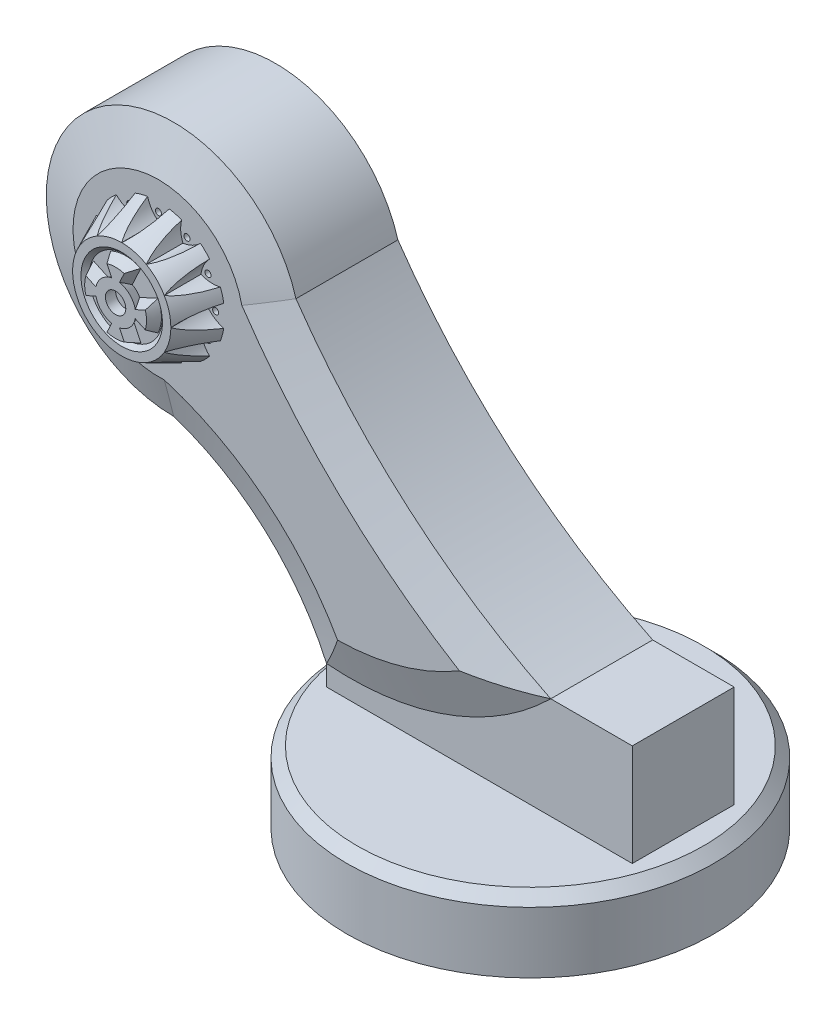
SolidWorks part; units mm, degrees
ref_plane "Front Plane" through (0, 0, 0) normal (0, 0, 1) x (1, 0, 0)
ref_plane "Top Plane" through (0, 0, 0) normal (0, 1, 0) x (1, 0, 0)
ref_plane "Right Plane" through (0, 0, 0) normal (1, 0, 0) x (0, 0, -1)
sketch "Sketch1" plane through (0, 0, 0) normal (0, 1, 0) x (1, 0, 0)
  circle A0 centre (0, 0) radius 90
  dimension "D1" = 180
extrude "Boss-Extrude1" add sketch "Sketch1" along normal blind 35
chamfer "Chamfer1" distance 5 angle 45 1 edges at (0, 35, 90)
sketch "Sketch2" plane through (0, 35, 0) normal (0, 1, 0) x (1, 0, 0)
  line L1 (-75, 25) -> (75, 25)
  line L2 (-75, 25) -> (-75, -25)
  line L3 (-75, -25) -> (75, -25)
  line L4 (75, 25) -> (75, -25)
  line L5 (-75, 25) -> (75, -25) construction
  line L6 (-75, -25) -> (75, 25) construction
  point P0 (0, 0)
  dimension "D1" = 150
  dimension "D2" = 50
extrude "Boss-Extrude2" add sketch "Sketch2" along normal blind 50
sketch "Sketch4" plane through (0, 0, 25) normal (0, 0, 1) x (1, 0, 0)
  line L0 (-75, 45) -> (-75, 85)
  line L1 (-75, 85) -> (-75, 35) construction
  line L2 (-75, 85) -> (35, 85)
  line L3 (-75, 85) -> (75, 85) construction
  arc A0 (-75, 45) -> (35, 85) centre (-63.4632, 184.5238) ccw
  dimension "D3" = 140
  dimension "D1" = 40
  dimension "D2" = 110
extrude "Cut-Extrude1" cut sketch "Sketch4" against normal blind 50
sketch "Sketch5" plane through (0, 0, 0) normal (0, 0, 1) x (1, 0, 0)
  arc A0 (-90, 192.5) -> (-150, 112.5) centre (-150, 175) ccw
  arc A1 (-150, 112.5) -> (-75, 45) centre (-189.0071, -6.2579) cw
  arc A2 (-90, 192.5) -> (35, 85) centre (177.4828, 377.1021) ccw
  arc A3 (-75, 45) -> (35, 85) centre (-63.4632, 184.5238) ccw
  dimension "D3" = 125
  dimension "D4" = 125
  dimension "D5" = 325
  dimension "D6" = 140
  dimension "D1" = 150
  dimension "D2" = 175
  dimension "D7" = 125
extrude "Boss-Extrude3" add sketch "Sketch5" along normal mid plane 50 separate body
sketch "Sketch6" plane through (0, 0, 25) normal (0, 0, 1) x (1, 0, 0)
  arc A4 (-75, 45) -> (-150, 112.5) centre (-189.0071, -6.2579) ccw
  arc A5 (-75, 45) -> (35, 85) centre (-63.4632, 184.5238) ccw
  arc A6 (-90, 192.5) -> (35, 85) centre (177.4828, 377.1021) ccw
  arc A7 (-90, 192.5) -> (-150, 112.5) centre (-150, 175) ccw
  arc A8 (-75, 45) -> (-150, 112.5) centre (-189.0071, -6.2579) ccw
  arc A9 (-75, 45) -> (35, 85) centre (-63.4632, 184.5238) ccw
  arc A10 (-90, 192.5) -> (35, 85) centre (177.4828, 377.1021) ccw
  arc A11 (-90, 192.5) -> (-150, 112.5) centre (-150, 175) ccw
  dimension "D1" = 0
extrude "Boss-Extrude5" add sketch "Sketch6" along normal blind 7.5 draft 70
sketch "Sketch7" plane through (0, 0, 32.5) normal (0, 0, 1) x (1, 0, 0)
  circle A0 centre (-150, 175) radius 32.5
  arc A1 (-109.0554, 183.8681) -> (-147.1527, 133.203) centre (-150, 175) ccw construction
  dimension "D1" = 65
extrude "Boss-Extrude6" add sketch "Sketch7" along normal blind 18 draft 25
sketch "Sketch9" plane through (0, 0, 50.5) normal (0, 0, 1) x (1, 0, 0)
  line L0 (-150, 175) -> (-150, 207.5) construction
  circle A0 centre (-150, 175) radius 32.5 construction
  arc A1 (-150, 199.1065) -> (-144.6801, 207.0616) centre (-159.1575, 210.9867) ccw
  circle A3 centre (-150, 175) radius 32.5
  arc A4 (-144.6801, 207.0616) -> (-155.3199, 207.0616) centre (-150, 175) ccw
  circle A5 centre (-150, 175) radius 24.1065 construction
  arc A6 (-150, 199.1065) -> (-155.3199, 207.0616) centre (-140.8425, 210.9867) cw
  dimension "D1" = 0
  dimension "D2" = 15
extrude "Cut-Extrude2" cut sketch "Sketch9" against normal up to surface (18 mm away) up to face at (-117.5, 175, 32.5)
sketch "Sketch10" plane through (0, 0, 32.5) normal (0, 0, 1) x (1, 0, 0)
  line L0 (-150, 199.1065) -> (-150, 207.0616) construction
  line L1 (-155.3199, 207.0616) -> (-144.6801, 207.0616) construction
  circle A2 centre (-150, 203.0841) radius 1.5
  dimension "D1" = 3
extrude "Cut-Extrude3" cut sketch "Sketch10" against normal blind 5
pattern_circular "CirPattern1" count 12 over 360 about axis through (-150, 175, 0) along (0, 0, 1) of "Cut-Extrude2", "Cut-Extrude3"
sketch "Sketch11" plane through (0, 0, 50.5) normal (0, 0, 1) x (1, 0, 0)
  circle A0 centre (-150, 175) radius 20
  dimension "D1" = 40
extrude "Cut-Extrude4" cut sketch "Sketch11" against normal blind 2 draft 45
sketch "Sketch12" plane through (0, 0, 48.5) normal (0, 0, 1) x (1, 0, 0)
  line L0 (-150, 175) -> (-150, 192.5) construction
  line L1 (-153.1696, 181.7973) -> (-157.3958, 190.8604)
  line L2 (-146.8304, 181.7973) -> (-142.6042, 190.8604)
  arc A0 (-146.8304, 181.7973) -> (-153.1696, 181.7973) centre (-150, 175) ccw
  arc A1 (-142.6042, 190.8604) -> (-157.3958, 190.8604) centre (-150, 175) ccw
  dimension "D1" = 15
  dimension "D2" = 35
  dimension "D3" = 25
extrude "Boss-Extrude7" add sketch "Sketch12" along normal blind 5 draft 25
pattern_circular "CirPattern2" count 4 over 360 about axis through (-150, 175, 0) along (0, 0, 1) of "Boss-Extrude7"
sketch "Sketch13" plane through (0, 0, 48.5) normal (0, 0, 1) x (1, 0, 0)
  circle A0 centre (-150, 175) radius 7.5
extrude "Boss-Extrude8" add sketch "Sketch13" along normal up to surface (5 mm away) draft 25
sketch "Sketch14" plane through (0, 0, 53.5) normal (0, 0, 1) x (1, 0, 0)
  circle A0 centre (-150, 175) radius 5
  dimension "D1" = 10
extrude "Cut-Extrude5" cut sketch "Sketch14" against normal up to surface (5 mm away) up to face at (-132, 175, 48.5)
sketch "Sketch15" plane through (0, 0, -25) normal (0, 0, -1) x (-1, 0, 0)
  circle A0 centre (150, 175) radius 15
  arc A1 (150, 112.5) -> (90, 192.5) centre (150, 175) ccw construction
  dimension "D1" = 30
extrude "Cut-Extrude6" cut sketch "Sketch15" against normal blind 25
sketch "Sketch16" plane through (0, 0, 0) normal (0, -1, 0) x (1, 0, 0)
  circle A0 centre (0, 0) radius 10.25
  dimension "D1" = 20.5
extrude "Cut-Extrude7" cut sketch "Sketch16" against normal blind 20.1
